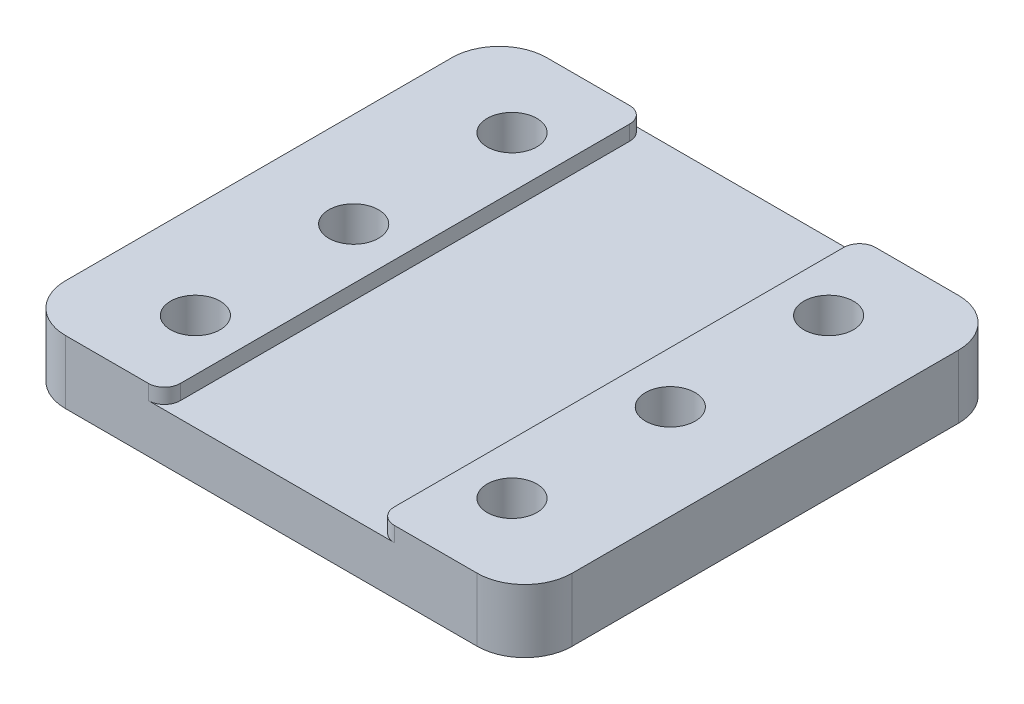
SolidWorks part; units mm, degrees
material "6061-T6 (SS)"
ref_plane "Front Plane" through (0, 0, 0) normal (0, 0, 1) x (1, 0, 0)
ref_plane "Top Plane" through (0, 0, 0) normal (0, 1, 0) x (1, 0, 0)
ref_plane "Right Plane" through (0, 0, 0) normal (1, 0, 0) x (0, 0, -1)
sketch "Sketch1" plane through (0, 0, 0) normal (0, 1, 0) x (1, 0, 0)
  line L0 (9.525, 48.26) -> (9.525, 0) construction
  line L1 (0, 0) -> (50.8, 0)
  line L2 (0, 0) -> (0, 48.26)
  line L3 (0, 48.26) -> (50.8, 48.26)
  line L4 (50.8, 0) -> (50.8, 48.26)
  line L9 (41.275, 0) -> (41.275, 48.26) construction
  line L10 (41.275, 24.13) -> (50.8, 24.13) construction
  line L13 (9.525, 24.13) -> (0, 24.13) construction
  circle A10 centre (9.525, 8.255) radius 2.4892
  circle A11 centre (9.525, 24.13) radius 2.4892
  circle A12 centre (9.525, 40.005) radius 2.4892
  circle A13 centre (41.275, 24.13) radius 2.4892
  circle A14 centre (41.275, 40.005) radius 2.4892
  circle A15 centre (41.275, 8.255) radius 2.4892
  dimension "D4" = 15.875
  dimension "D5" = 4.9784
  dimension "D3" = 15.875
  dimension "D1" = 50.8
  dimension "D2" = 48.26
  dimension "D6" = 9.525
extrude "Boss-Extrude1" add sketch "Sketch1" along normal mid plane 6.35
fillet "Fillet1" radius 4.7625 4 edges at (0, 0, -48.26) (50.8, 0, -48.26) (0, 0, 0) (50.8, 0, 0)
sketch "Sketch3" plane through (0, 3.175, 0) normal (0, 1, 0) x (1, 0, 0)
  line L0 (4.7625, 48.26) -> (46.0375, 48.26) construction
  line L1 (14.675, 0) -> (36.125, 0)
  line L2 (14.675, 0) -> (14.675, 48.26)
  line L3 (14.675, 48.26) -> (36.125, 48.26)
  line L4 (36.125, 0) -> (36.125, 48.26)
  line L5 (25.4, 48.26) -> (25.4, 0) construction
  line L7 (4.7625, 0) -> (46.0375, 0) construction
  dimension "D1" = 21.45
extrude "Cut-Extrude2" cut sketch "Sketch3" against normal blind 1.5
fillet "Fillet2" radius 1.6 4 edges at (36.125, 2.425, 0) (14.675, 2.425, 0) (36.125, 2.425, -48.26) (14.675, 2.425, -48.26)
equation "\"D1@Sketch3\"=18.25mm+3.2mm"
equation "\"D1@Cut-Extrude2\"=(3.6mm - 2.1mm)"
equation "\"D1@Fillet2\"=1.6mm"
